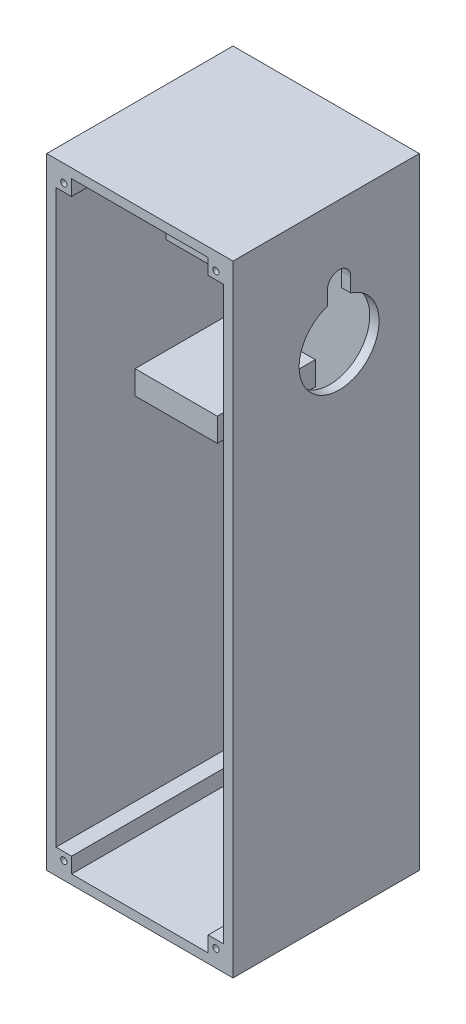
SolidWorks part; units mm, degrees
ref_plane "Płaszczyzna przednia" through (0, 0, 0) normal (0, 0, 1) x (1, 0, 0)
ref_plane "Płaszczyzna górna" through (0, 0, 0) normal (0, 1, 0) x (1, 0, 0)
ref_plane "Płaszczyzna prawa" through (0, 0, 0) normal (1, 0, 0) x (0, 0, -1)
sketch "Szkic1" plane through (0, 0, 0) normal (0, 1, 0) x (1, 0, 0)
  line L1 (0, 0) -> (60, 0)
  line L2 (0, 0) -> (0, 60)
  line L3 (0, 60) -> (60, 60)
  line L4 (60, 0) -> (60, 60)
  dimension "D1" = 60
  dimension "D2" = 60
extrude "Dodanie-wyciągnięcie1" add sketch "Szkic1" along normal blind 200
shell "Skorupa1" thickness 3
sketch "Szkic2" plane through (0, 0, -57) normal (0, 0, 1) x (1, 0, 0)
  line L1 (3, 197) -> (8, 197)
  line L2 (3, 197) -> (3, 192)
  line L3 (3, 192) -> (8, 192)
  line L4 (8, 197) -> (8, 192)
  circle A0 centre (5.5, 194.5) radius 1
  dimension "D3" = 2
  dimension "D1" = 5
  dimension "D2" = 5
extrude "Dodanie-wyciągnięcie2" add sketch "Szkic2" along normal blind 57
sketch "Szkic4" plane through (0, 0, 0) normal (0, 0, 1) x (1, 0, 0)
  line L1 (57, 197) -> (52, 197)
  line L2 (57, 197) -> (57, 192)
  line L3 (57, 192) -> (52, 192)
  line L4 (52, 197) -> (52, 192)
  circle A0 centre (54.5, 194.5) radius 1
  dimension "D2" = 2
  dimension "D1" = 5
extrude "Dodanie-wyciągnięcie3" add sketch "Szkic4" against normal blind 57
sketch "Szkic5" plane through (0, 0, -57) normal (0, 0, 1) x (1, 0, 0)
  line L1 (3, 3) -> (8, 3)
  line L2 (3, 3) -> (3, 8)
  line L3 (3, 8) -> (8, 8)
  line L4 (8, 3) -> (8, 8)
  circle A0 centre (5.5, 5.5) radius 1
  dimension "D2" = 2
  dimension "D1" = 5
extrude "Dodanie-wyciągnięcie4" add sketch "Szkic5" along normal blind 57
sketch "Szkic6" plane through (0, 0, -57) normal (0, 0, 1) x (1, 0, 0)
  line L1 (57, 3) -> (52, 3)
  line L2 (57, 3) -> (57, 8)
  line L3 (57, 8) -> (52, 8)
  line L4 (52, 3) -> (52, 8)
  circle A0 centre (54.5, 5.5) radius 1
  dimension "D2" = 2
  dimension "D1" = 5
extrude "Dodanie-wyciągnięcie6" add sketch "Szkic6" along normal blind 57
sketch "Szkic9" plane through (60, 0, 0) normal (1, 0, 0) x (0, 0, -1)
  line L0 (0, 200) -> (60, 200) construction
  line L1 (0, 200) -> (0, 0) construction
  circle A0 centre (34.18, 159.82) radius 12.875
  dimension "D1" = 25.75
  dimension "D2" = 40.18
  dimension "D3" = 34.18
extrude "Wytnij-wyciągnięcie1" cut sketch "Szkic9" against normal blind 3
sketch "Szkic10" plane through (3, 0, 0) normal (1, 0, 0) x (0, 0, -1)
  line L1 (25.45, 169.76) -> (57, 169.76)
  line L2 (25.45, 169.76) -> (25.45, 177.36)
  line L3 (25.45, 177.36) -> (57, 177.36)
  line L4 (57, 169.76) -> (57, 177.36)
  line L6 (0, 197) -> (57, 197) construction
  line L7 (25.45, 128.76) -> (57, 128.76)
  line L8 (25.45, 128.76) -> (25.45, 121.16)
  line L9 (25.45, 121.16) -> (57, 121.16)
  line L10 (57, 128.76) -> (57, 121.16)
  line L12 (0, 192) -> (57, 192) construction
  line L13 (0, 192) -> (0, 8) construction
  dimension "D1" = 31.55
  dimension "D2" = 7.6
  dimension "D3" = 27.24
  dimension "D4" = 63.24
  dimension "D6" = 7.6
  dimension "D7" = 25.45
  dimension "D8" = 25.45
extrude "Dodanie-wyciągnięcie7" add sketch "Szkic10" along normal blind 26.5
sketch "Szkic13" plane through (29.5, 0, 0) normal (1, 0, 0) x (0, 0, -1)
  line L0 (25.45, 177.36) -> (25.45, 169.76) construction
  line L5 (57, 177.36) -> (25.45, 177.36) construction
  circle A0 centre (39.21, 174.36) radius 1.5
  circle A1 centre (29.42, 174.36) radius 1.5
  dimension "D1" = 3
  dimension "D2" = 3.97
  dimension "D3" = 3
  dimension "D5" = 3
  dimension "D6" = 3
  dimension "D4" = 13.76
extrude "Wytnij-wyciągnięcie4" cut sketch "Szkic13" against normal blind 5
sketch "Szkic14" plane through (29.5, 0, 0) normal (1, 0, 0) x (0, 0, -1)
  line L0 (25.45, 128.76) -> (25.45, 121.16) construction
  line L6 (25.45, 121.16) -> (57, 121.16) construction
  circle A0 centre (39.21, 124.16) radius 1.5
  circle A1 centre (29.42, 124.16) radius 1.5
  dimension "D1" = 3
  dimension "D2" = 3.97
  dimension "D3" = 3
  dimension "D5" = 3
  dimension "D6" = 3
  dimension "D4" = 13.76
sketch "Szkic15" plane through (0, 177.36, 0) normal (0, 1, 0) x (1, 0, 0)
  line L0 (29.5, 25.45) -> (13, 25.45)
  line L1 (29.5, 25.45) -> (3, 25.45) construction
  line L2 (13, 25.45) -> (3, 25.45)
  line L3 (3, 25.45) -> (3, 49.45)
  line L4 (3, 57) -> (3, 25.45) construction
  line L5 (3, 49.45) -> (13, 25.45)
  dimension "D1" = 16.5
  dimension "D2" = 24
extrude "Wytnij-wyciągnięcie7" cut sketch "Szkic15" against normal blind 10 contours L2 L3 L5
extrude "Wytnij-wyciągnięcie8" cut sketch "Szkic14" against normal blind 5
sketch "Szkic17" plane through (60, 0, 0) normal (1, 0, 0) x (0, 0, -1)
  line L0 (34.18, 172.1368) -> (34.18, 146.945) construction
  line L2 (30.43, 172.445) -> (30.43, 176.755)
  line L3 (37.93, 172.445) -> (37.93, 176.755)
  line L4 (37.93, 172.445) -> (37.93, 172.1368)
  line L5 (37.93, 172.1368) -> (30.43, 172.1368)
  line L6 (30.43, 172.1368) -> (30.43, 172.445)
  circle A0 centre (34.18, 159.82) radius 12.875 construction
  arc A1 (30.43, 176.755) -> (37.93, 176.755) centre (34.18, 176.755) cw
  point P8 (34.18, 172.445)
  dimension "D1" = 7.5
  dimension "D2" = 4.31
  dimension "D3" = 4.31
extrude "Wytnij-wyciągnięcie10" cut sketch "Szkic17" against normal blind 10
